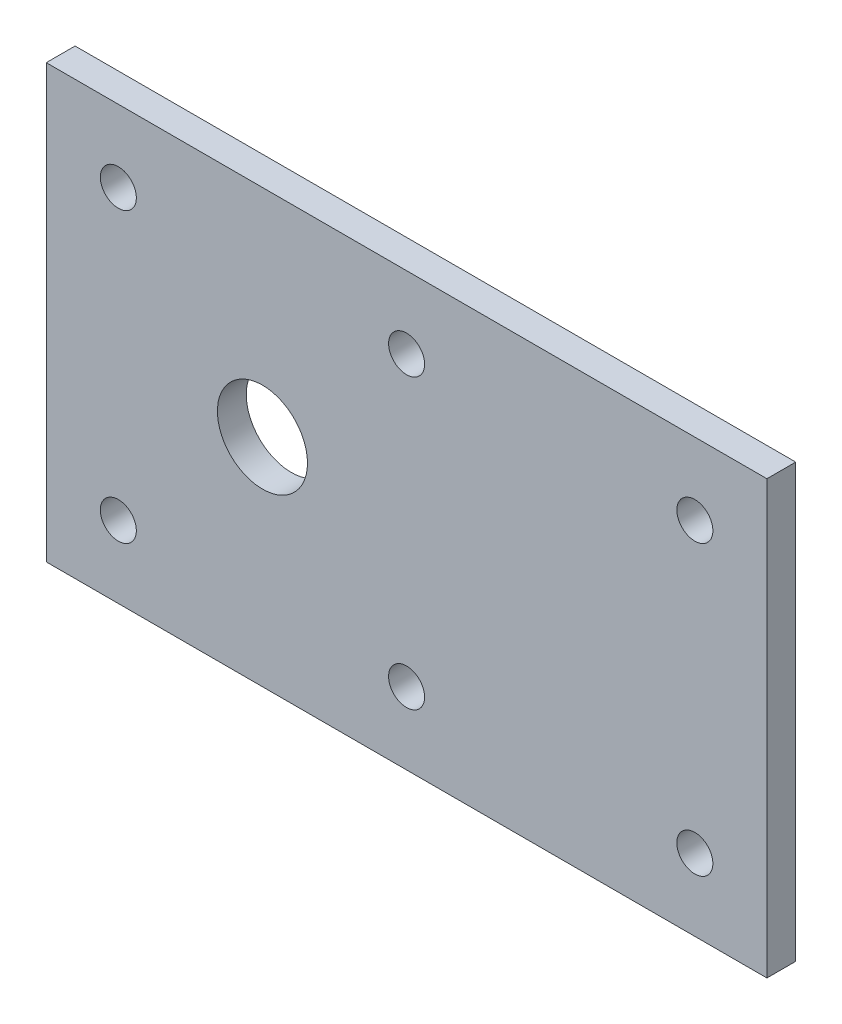
SolidWorks part; units mm, degrees
ref_plane "Front Plane" through (0, 0, 0) normal (0, 0, 1) x (1, 0, 0)
ref_plane "Top Plane" through (0, 0, 0) normal (0, 1, 0) x (1, 0, 0)
ref_plane "Right Plane" through (0, 0, 0) normal (1, 0, 0) x (0, 0, -1)
sketch "Sketch1" plane through (0, 0, 0) normal (0, 0, 1) x (1, 0, 0)
  line L0 (-60, 0) -> (140, 0) construction
  line L1 (140, 60) -> (-60, 60)
  line L2 (140, 60) -> (140, -60)
  line L3 (140, -60) -> (-60, -60)
  line L4 (-60, 60) -> (-60, -60)
  point P0 (0, 0)
  dimension "D1" = 200
  dimension "D2" = 120
  dimension "D3" = 60
extrude "Boss-Extrude1" add sketch "Sketch1" along normal blind 8
sketch "Sketch2" plane through (0, 0, 8) normal (0, 0, 1) x (1, 0, 0)
  line L0 (-60, 60) -> (-60, -60) construction
  line L1 (140, 60) -> (-60, 60) construction
  circle A0 centre (-40, 40) radius 5
  dimension "D1" = 20
  dimension "D3" = 10
  dimension "D2" = 20
extrude "Cut-Extrude1" cut sketch "Sketch2" against normal through all
pattern_linear "LPattern1" count 3 spacing 80 along (1, 0, 0) count 2 spacing 80 along (0, -1, 0) of "Cut-Extrude1"
sketch "Sketch3" plane through (0, 0, 8) normal (0, 0, 1) x (1, 0, 0)
  circle A0 centre (0, 0) radius 12.5
  dimension "D1" = 25
extrude "Cut-Extrude2" cut sketch "Sketch3" against normal through all
